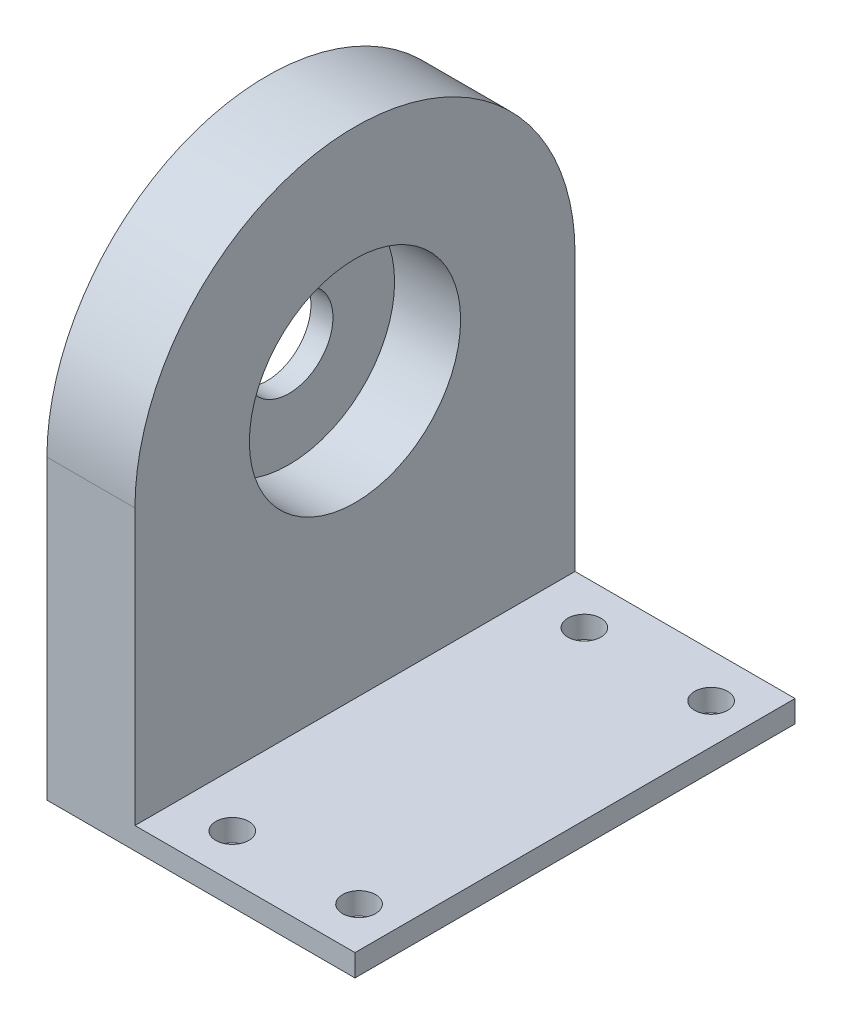
SolidWorks part; units mm, degrees
ref_plane "Front Plane" through (0, 0, 0) normal (0, 0, 1) x (1, 0, 0)
ref_plane "Top Plane" through (0, 0, 0) normal (0, 1, 0) x (1, 0, 0)
ref_plane "Right Plane" through (0, 0, 0) normal (1, 0, 0) x (0, 0, -1)
sketch "Sketch1" plane through (0, 0, 0) normal (1, 0, 0) x (0, 0, -1)
  line L2 (-25.25, 9.0833) -> (-25.25, -17.9167)
  line L3 (-25.25, -17.9167) -> (14.75, -17.9167)
  line L4 (14.75, 9.0833) -> (14.75, -17.9167)
  arc A0 (14.75, 9.0833) -> (-25.25, 9.0833) centre (-5.25, 9.0833) ccw
  dimension "D1" = 27
  dimension "D2" = 40
extrude "Boss-Extrude1" add sketch "Sketch1" along normal blind 6 and the other way blind 2
sketch "Sketch2" plane through (6, 0, 0) normal (1, 0, 0) x (0, 0, -1)
  line L0 (-25.25, 9.0833) -> (14.75, 9.0833)
  circle A0 centre (-5.25, 9.0833) radius 9.6
  dimension "D1" = 19.2
extrude "Cut-Extrude1" cut sketch "Sketch2" against normal blind 6 contours L0 A0 | L0 A0
sketch "Sketch3" plane through (6, 0, 0) normal (1, 0, 0) x (0, 0, -1)
  circle A0 centre (-5.25, 9.0833) radius 4
  dimension "D1" = 8
extrude "Cut-Extrude2" cut sketch "Sketch3" against normal blind 10
sketch "Sketch4" plane through (6, 0, 0) normal (1, 0, 0) x (0, 0, -1)
  line L0 (14.75, -17.9167) -> (14.75, 9.0833) construction
  line L1 (-25.25, -17.9167) -> (14.75, -17.9167)
  line L2 (-25.25, -17.9167) -> (-25.25, -15.9167)
  line L3 (-25.25, -15.9167) -> (14.75, -15.9167)
  line L4 (14.75, -17.9167) -> (14.75, -15.9167)
  dimension "D1" = 2
extrude "Boss-Extrude2" add sketch "Sketch4" along normal blind 20
sketch "Sketch5" plane through (0, -15.9167, 0) normal (0, 1, 0) x (1, 0, 0)
  line L0 (26, 14.75) -> (6, 14.75) construction
  line L1 (26, -25.25) -> (6, -25.25) construction
  circle A0 centre (10.8479, 10.75) radius 1.5
  circle A1 centre (22.3687, 10.75) radius 1.5
  circle A2 centre (10.8479, -21.25) radius 1.5
  circle A3 centre (22.3687, -21.25) radius 1.5
  dimension "D1" = 3
  dimension "D2" = 3
  dimension "D3" = 3
  dimension "D4" = 3
  dimension "D5" = 4
  dimension "D6" = 4
  dimension "D7" = 4
  dimension "D8" = 4
extrude "Cut-Extrude3" cut sketch "Sketch5" against normal blind 10 contours A0 | A1 | A3 | A2
